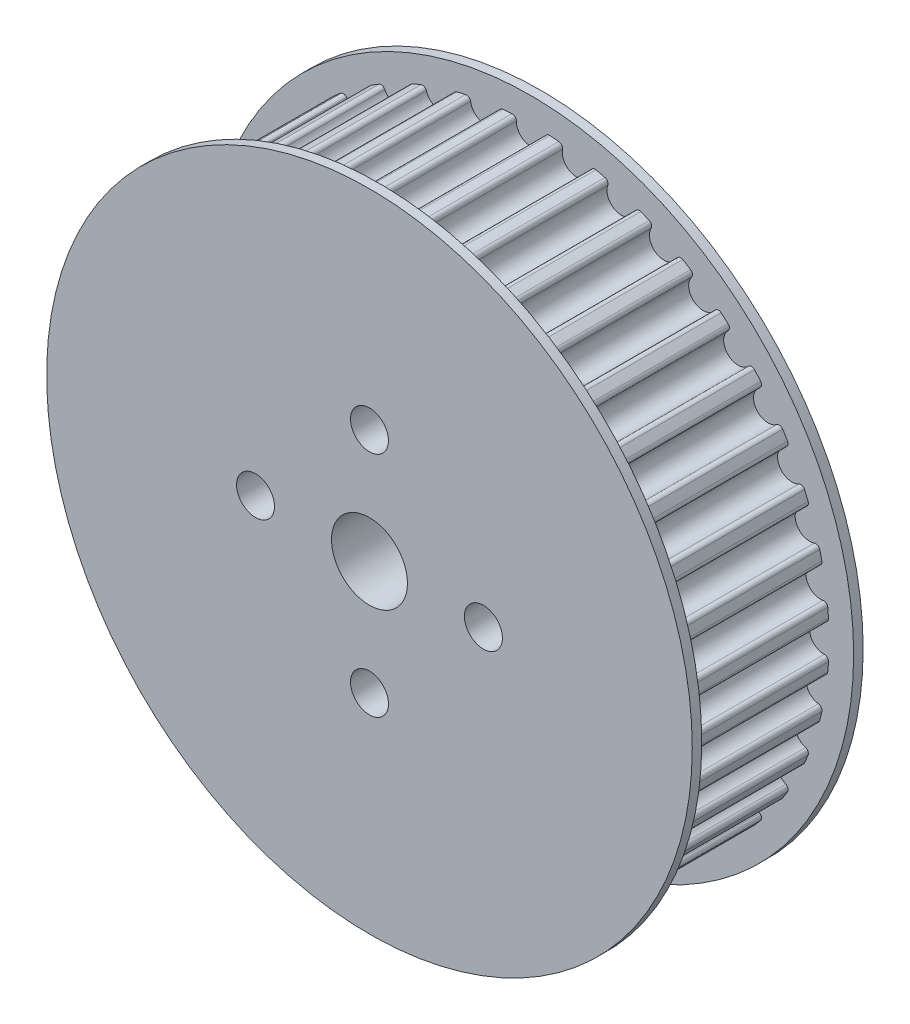
SolidWorks part; units mm, degrees
ref_plane "Front Plane" through (0, 0, 0) normal (0, 0, 1) x (1, 0, 0)
ref_plane "Top Plane" through (0, 0, 0) normal (0, 1, 0) x (1, 0, 0)
ref_plane "Right Plane" through (0, 0, 0) normal (1, 0, 0) x (0, 0, -1)
sketch "Sketch1" plane through (0, 0, 0) normal (0, 0, 1) x (1, 0, 0)
  line L0 (0, 0) -> (0, 52.0511) construction
  line L1 (0, 0) -> (78.6588, 0) construction
  line L2 (0, 0) -> (7.0914, 44.7731) construction
  arc A2 (0, 29.35) -> (1.5246, 30.9088) centre (0, 30.875) ccw
  arc A3 (1.9816, 31.3474) -> (1.5246, 30.9088) centre (1.9545, 30.9183) ccw
  arc A4 (3.3293, 30.7667) -> (4.5914, 28.9887) centre (4.8299, 30.4949) ccw
  arc A5 (3.3293, 30.7667) -> (2.9466, 31.2715) centre (2.9062, 30.8434) ccw
  arc A6 (2.9466, 31.2715) -> (1.9816, 31.3474) centre (0, 0) ccw
  arc A7 (4.5914, 28.9887) -> (6.3411, 30.2897) centre (4.8299, 30.4949) ccw
  arc A8 (6.8611, 30.6515) -> (6.3411, 30.2897) centre (6.7671, 30.2319) ccw
  arc A9 (7.8022, 30.4255) -> (6.8611, 30.6515) centre (0, 0) ccw
  arc A10 (8.1013, 29.8671) -> (7.8022, 30.4255) centre (7.6954, 30.009) ccw
  arc A11 (8.1013, 29.8671) -> (9.0696, 27.9135) centre (9.5409, 29.3639) ccw
  arc A12 (9.0696, 27.9135) -> (11.0013, 28.9248) centre (9.5409, 29.3639) ccw
  arc A13 (11.5715, 29.2008) -> (11.0013, 28.9248) centre (11.4131, 28.8011) ccw
  arc A14 (12.4658, 28.8304) -> (11.5715, 29.2008) centre (0, 0) ccw
  arc A15 (12.6738, 28.2321) -> (12.4658, 28.8304) centre (12.2951, 28.4357) ccw
  arc A16 (12.6738, 28.2321) -> (13.3246, 26.151) centre (14.017, 27.5098) ccw
  arc A17 (13.3246, 26.151) -> (15.3907, 26.8477) centre (14.017, 27.5098) ccw
  arc A18 (15.9971, 27.0311) -> (15.3907, 26.8477) centre (15.7781, 26.6611) ccw
  arc A19 (16.8224, 26.5254) -> (15.9971, 27.0311) centre (0, 0) ccw
  arc A20 (16.9343, 25.9019) -> (16.8224, 26.5254) centre (16.5921, 26.1623) ccw
  arc A21 (16.9343, 25.9019) -> (17.2515, 23.7446) centre (18.1479, 24.9784) ccw
  arc A22 (17.2515, 23.7446) -> (19.4012, 24.1096) centre (18.1479, 24.9784) ccw
  arc A23 (20.0287, 24.1958) -> (19.4012, 24.1096) centre (19.7546, 23.8646) ccw
  arc A24 (20.7647, 23.5672) -> (20.0287, 24.1958) centre (0, 0) ccw
  arc A25 (20.7777, 22.9339) -> (20.7647, 23.5672) centre (20.4805, 23.2446) ccw
  arc A26 (20.7777, 22.9339) -> (20.7536, 20.7536) centre (21.8319, 21.8319) ccw
  arc A27 (20.7536, 20.7536) -> (22.9339, 20.7777) centre (21.8319, 21.8319) ccw
  arc A28 (23.5672, 20.7647) -> (22.9339, 20.7777) centre (23.2446, 20.4805) ccw
  arc A29 (24.1958, 20.0287) -> (23.5672, 20.7647) centre (0, 0) ccw
  arc A30 (24.1096, 19.4012) -> (24.1958, 20.0287) centre (23.8646, 19.7546) ccw
  arc A31 (24.1096, 19.4012) -> (23.7446, 17.2515) centre (24.9784, 18.1479) ccw
  arc A32 (23.7446, 17.2515) -> (25.9019, 16.9343) centre (24.9784, 18.1479) ccw
  arc A33 (26.5254, 16.8224) -> (25.9019, 16.9343) centre (26.1623, 16.5921) ccw
  arc A34 (27.0311, 15.9971) -> (26.5254, 16.8224) centre (0, 0) ccw
  arc A35 (26.8477, 15.3907) -> (27.0311, 15.9971) centre (26.6611, 15.7781) ccw
  arc A36 (26.8477, 15.3907) -> (26.151, 13.3246) centre (27.5098, 14.017) ccw
  arc A37 (26.151, 13.3246) -> (28.2321, 12.6738) centre (27.5098, 14.017) ccw
  arc A38 (28.8304, 12.4658) -> (28.2321, 12.6738) centre (28.4357, 12.2951) ccw
  arc A39 (29.2008, 11.5715) -> (28.8304, 12.4658) centre (0, 0) ccw
  arc A40 (28.9248, 11.0013) -> (29.2008, 11.5715) centre (28.8011, 11.4131) ccw
  arc A41 (28.9248, 11.0013) -> (27.9135, 9.0696) centre (29.3639, 9.5409) ccw
  arc A42 (27.9135, 9.0696) -> (29.8671, 8.1013) centre (29.3639, 9.5409) ccw
  arc A43 (30.4255, 7.8022) -> (29.8671, 8.1013) centre (30.009, 7.6954) ccw
  arc A44 (30.6515, 6.8611) -> (30.4255, 7.8022) centre (0, 0) ccw
  arc A45 (30.2897, 6.3411) -> (30.6515, 6.8611) centre (30.2319, 6.7671) ccw
  arc A46 (30.2897, 6.3411) -> (28.9887, 4.5914) centre (30.4949, 4.8299) ccw
  arc A47 (28.9887, 4.5914) -> (30.7667, 3.3293) centre (30.4949, 4.8299) ccw
  arc A48 (31.2715, 2.9466) -> (30.7667, 3.3293) centre (30.8434, 2.9062) ccw
  arc A49 (31.3474, 1.9816) -> (31.2715, 2.9466) centre (0, 0) ccw
  arc A50 (30.9088, 1.5246) -> (31.3474, 1.9816) centre (30.9183, 1.9545) ccw
  arc A51 (30.9088, 1.5246) -> (29.35, 0) centre (30.875, 0) ccw
  arc A52 (29.35, 0) -> (30.9088, -1.5246) centre (30.875, 0) ccw
  arc A53 (31.3474, -1.9816) -> (30.9088, -1.5246) centre (30.9183, -1.9545) ccw
  arc A54 (31.2715, -2.9466) -> (31.3474, -1.9816) centre (0, 0) ccw
  arc A55 (30.7667, -3.3293) -> (31.2715, -2.9466) centre (30.8434, -2.9062) ccw
  arc A56 (30.7667, -3.3293) -> (28.9887, -4.5914) centre (30.4949, -4.8299) ccw
  arc A57 (28.9887, -4.5914) -> (30.2897, -6.3411) centre (30.4949, -4.8299) ccw
  arc A58 (30.6515, -6.8611) -> (30.2897, -6.3411) centre (30.2319, -6.7671) ccw
  arc A59 (30.4255, -7.8022) -> (30.6515, -6.8611) centre (0, 0) ccw
  arc A60 (29.8671, -8.1013) -> (30.4255, -7.8022) centre (30.009, -7.6954) ccw
  arc A61 (29.8671, -8.1013) -> (27.9135, -9.0696) centre (29.3639, -9.5409) ccw
  arc A62 (27.9135, -9.0696) -> (28.9248, -11.0013) centre (29.3639, -9.5409) ccw
  arc A63 (29.2008, -11.5715) -> (28.9248, -11.0013) centre (28.8011, -11.4131) ccw
  arc A64 (28.8304, -12.4658) -> (29.2008, -11.5715) centre (0, 0) ccw
  arc A65 (28.2321, -12.6738) -> (28.8304, -12.4658) centre (28.4357, -12.2951) ccw
  arc A66 (28.2321, -12.6738) -> (26.151, -13.3246) centre (27.5098, -14.017) ccw
  arc A67 (26.151, -13.3246) -> (26.8477, -15.3907) centre (27.5098, -14.017) ccw
  arc A68 (27.0311, -15.9971) -> (26.8477, -15.3907) centre (26.6611, -15.7781) ccw
  arc A69 (26.5254, -16.8224) -> (27.0311, -15.9971) centre (0, 0) ccw
  arc A70 (25.9019, -16.9343) -> (26.5254, -16.8224) centre (26.1623, -16.5921) ccw
  arc A71 (25.9019, -16.9343) -> (23.7446, -17.2515) centre (24.9784, -18.1479) ccw
  arc A72 (23.7446, -17.2515) -> (24.1096, -19.4012) centre (24.9784, -18.1479) ccw
  arc A73 (24.1958, -20.0287) -> (24.1096, -19.4012) centre (23.8646, -19.7546) ccw
  arc A74 (23.5672, -20.7647) -> (24.1958, -20.0287) centre (0, 0) ccw
  arc A75 (22.9339, -20.7777) -> (23.5672, -20.7647) centre (23.2446, -20.4805) ccw
  arc A76 (22.9339, -20.7777) -> (20.7536, -20.7536) centre (21.8319, -21.8319) ccw
  arc A77 (20.7536, -20.7536) -> (20.7777, -22.9339) centre (21.8319, -21.8319) ccw
  arc A78 (20.7647, -23.5672) -> (20.7777, -22.9339) centre (20.4805, -23.2446) ccw
  arc A79 (20.0287, -24.1958) -> (20.7647, -23.5672) centre (0, 0) ccw
  arc A80 (19.4012, -24.1096) -> (20.0287, -24.1958) centre (19.7546, -23.8646) ccw
  arc A81 (19.4012, -24.1096) -> (17.2515, -23.7446) centre (18.1479, -24.9784) ccw
  arc A82 (17.2515, -23.7446) -> (16.9343, -25.9019) centre (18.1479, -24.9784) ccw
  arc A83 (16.8224, -26.5254) -> (16.9343, -25.9019) centre (16.5921, -26.1623) ccw
  arc A84 (15.9971, -27.0311) -> (16.8224, -26.5254) centre (0, 0) ccw
  arc A85 (15.3907, -26.8477) -> (15.9971, -27.0311) centre (15.7781, -26.6611) ccw
  arc A86 (15.3907, -26.8477) -> (13.3246, -26.151) centre (14.017, -27.5098) ccw
  arc A87 (13.3246, -26.151) -> (12.6738, -28.2321) centre (14.017, -27.5098) ccw
  arc A88 (12.4658, -28.8304) -> (12.6738, -28.2321) centre (12.2951, -28.4357) ccw
  arc A89 (11.5715, -29.2008) -> (12.4658, -28.8304) centre (0, 0) ccw
  arc A90 (11.0013, -28.9248) -> (11.5715, -29.2008) centre (11.4131, -28.8011) ccw
  arc A91 (11.0013, -28.9248) -> (9.0696, -27.9135) centre (9.5409, -29.3639) ccw
  arc A92 (9.0696, -27.9135) -> (8.1013, -29.8671) centre (9.5409, -29.3639) ccw
  arc A93 (7.8022, -30.4255) -> (8.1013, -29.8671) centre (7.6954, -30.009) ccw
  arc A94 (6.8611, -30.6515) -> (7.8022, -30.4255) centre (0, 0) ccw
  arc A95 (6.3411, -30.2897) -> (6.8611, -30.6515) centre (6.7671, -30.2319) ccw
  arc A96 (6.3411, -30.2897) -> (4.5914, -28.9887) centre (4.8299, -30.4949) ccw
  arc A97 (4.5914, -28.9887) -> (3.3293, -30.7667) centre (4.8299, -30.4949) ccw
  arc A98 (2.9466, -31.2715) -> (3.3293, -30.7667) centre (2.9062, -30.8434) ccw
  arc A99 (1.9816, -31.3474) -> (2.9466, -31.2715) centre (0, 0) ccw
  arc A100 (1.5246, -30.9088) -> (1.9816, -31.3474) centre (1.9545, -30.9183) ccw
  arc A101 (1.5246, -30.9088) -> (0, -29.35) centre (0, -30.875) ccw
  arc A102 (0, -29.35) -> (-1.5246, -30.9088) centre (0, -30.875) ccw
  arc A103 (-1.9816, -31.3474) -> (-1.5246, -30.9088) centre (-1.9545, -30.9183) ccw
  arc A104 (-2.9466, -31.2715) -> (-1.9816, -31.3474) centre (0, 0) ccw
  arc A105 (-3.3293, -30.7667) -> (-2.9466, -31.2715) centre (-2.9062, -30.8434) ccw
  arc A106 (-3.3293, -30.7667) -> (-4.5914, -28.9887) centre (-4.8299, -30.4949) ccw
  arc A107 (-4.5914, -28.9887) -> (-6.3411, -30.2897) centre (-4.8299, -30.4949) ccw
  arc A108 (-6.8611, -30.6515) -> (-6.3411, -30.2897) centre (-6.7671, -30.2319) ccw
  arc A109 (-7.8022, -30.4255) -> (-6.8611, -30.6515) centre (0, 0) ccw
  arc A110 (-8.1013, -29.8671) -> (-7.8022, -30.4255) centre (-7.6954, -30.009) ccw
  arc A111 (-8.1013, -29.8671) -> (-9.0696, -27.9135) centre (-9.5409, -29.3639) ccw
  arc A112 (-9.0696, -27.9135) -> (-11.0013, -28.9248) centre (-9.5409, -29.3639) ccw
  arc A113 (-11.5715, -29.2008) -> (-11.0013, -28.9248) centre (-11.4131, -28.8011) ccw
  arc A114 (-12.4658, -28.8304) -> (-11.5715, -29.2008) centre (0, 0) ccw
  arc A115 (-12.6738, -28.2321) -> (-12.4658, -28.8304) centre (-12.2951, -28.4357) ccw
  arc A116 (-12.6738, -28.2321) -> (-13.3246, -26.151) centre (-14.017, -27.5098) ccw
  arc A117 (-13.3246, -26.151) -> (-15.3907, -26.8477) centre (-14.017, -27.5098) ccw
  arc A118 (-15.9971, -27.0311) -> (-15.3907, -26.8477) centre (-15.7781, -26.6611) ccw
  arc A119 (-16.8224, -26.5254) -> (-15.9971, -27.0311) centre (0, 0) ccw
  arc A120 (-16.9343, -25.9019) -> (-16.8224, -26.5254) centre (-16.5921, -26.1623) ccw
  arc A121 (-16.9343, -25.9019) -> (-17.2515, -23.7446) centre (-18.1479, -24.9784) ccw
  arc A122 (-17.2515, -23.7446) -> (-19.4012, -24.1096) centre (-18.1479, -24.9784) ccw
  arc A123 (-20.0287, -24.1958) -> (-19.4012, -24.1096) centre (-19.7546, -23.8646) ccw
  arc A124 (-20.7647, -23.5672) -> (-20.0287, -24.1958) centre (0, 0) ccw
  arc A125 (-20.7777, -22.9339) -> (-20.7647, -23.5672) centre (-20.4805, -23.2446) ccw
  arc A126 (-20.7777, -22.9339) -> (-20.7536, -20.7536) centre (-21.8319, -21.8319) ccw
  arc A127 (-20.7536, -20.7536) -> (-22.9339, -20.7777) centre (-21.8319, -21.8319) ccw
  arc A128 (-23.5672, -20.7647) -> (-22.9339, -20.7777) centre (-23.2446, -20.4805) ccw
  arc A129 (-24.1958, -20.0287) -> (-23.5672, -20.7647) centre (0, 0) ccw
  arc A130 (-24.1096, -19.4012) -> (-24.1958, -20.0287) centre (-23.8646, -19.7546) ccw
  arc A131 (-24.1096, -19.4012) -> (-23.7446, -17.2515) centre (-24.9784, -18.1479) ccw
  arc A132 (-23.7446, -17.2515) -> (-25.9019, -16.9343) centre (-24.9784, -18.1479) ccw
  arc A133 (-26.5254, -16.8224) -> (-25.9019, -16.9343) centre (-26.1623, -16.5921) ccw
  arc A134 (-27.0311, -15.9971) -> (-26.5254, -16.8224) centre (0, 0) ccw
  arc A135 (-26.8477, -15.3907) -> (-27.0311, -15.9971) centre (-26.6611, -15.7781) ccw
  arc A136 (-26.8477, -15.3907) -> (-26.151, -13.3246) centre (-27.5098, -14.017) ccw
  arc A137 (-26.151, -13.3246) -> (-28.2321, -12.6738) centre (-27.5098, -14.017) ccw
  arc A138 (-28.8304, -12.4658) -> (-28.2321, -12.6738) centre (-28.4357, -12.2951) ccw
  arc A139 (-29.2008, -11.5715) -> (-28.8304, -12.4658) centre (0, 0) ccw
  arc A140 (-28.9248, -11.0013) -> (-29.2008, -11.5715) centre (-28.8011, -11.4131) ccw
  arc A141 (-28.9248, -11.0013) -> (-27.9135, -9.0696) centre (-29.3639, -9.5409) ccw
  arc A142 (-27.9135, -9.0696) -> (-29.8671, -8.1013) centre (-29.3639, -9.5409) ccw
  arc A143 (-30.4255, -7.8022) -> (-29.8671, -8.1013) centre (-30.009, -7.6954) ccw
  arc A144 (-30.6515, -6.8611) -> (-30.4255, -7.8022) centre (0, 0) ccw
  arc A145 (-30.2897, -6.3411) -> (-30.6515, -6.8611) centre (-30.2319, -6.7671) ccw
  arc A146 (-30.2897, -6.3411) -> (-28.9887, -4.5914) centre (-30.4949, -4.8299) ccw
  arc A147 (-28.9887, -4.5914) -> (-30.7667, -3.3293) centre (-30.4949, -4.8299) ccw
  arc A148 (-31.2715, -2.9466) -> (-30.7667, -3.3293) centre (-30.8434, -2.9062) ccw
  arc A149 (-31.3474, -1.9816) -> (-31.2715, -2.9466) centre (0, 0) ccw
  arc A150 (-30.9088, -1.5246) -> (-31.3474, -1.9816) centre (-30.9183, -1.9545) ccw
  arc A151 (-30.9088, -1.5246) -> (-29.35, 0) centre (-30.875, 0) ccw
  arc A152 (-29.35, 0) -> (-30.9088, 1.5246) centre (-30.875, 0) ccw
  arc A153 (-31.3474, 1.9816) -> (-30.9088, 1.5246) centre (-30.9183, 1.9545) ccw
  arc A154 (-31.2715, 2.9466) -> (-31.3474, 1.9816) centre (0, 0) ccw
  arc A155 (-30.7667, 3.3293) -> (-31.2715, 2.9466) centre (-30.8434, 2.9062) ccw
  arc A156 (-30.7667, 3.3293) -> (-28.9887, 4.5914) centre (-30.4949, 4.8299) ccw
  arc A157 (-28.9887, 4.5914) -> (-30.2897, 6.3411) centre (-30.4949, 4.8299) ccw
  arc A158 (-30.6515, 6.8611) -> (-30.2897, 6.3411) centre (-30.2319, 6.7671) ccw
  arc A159 (-30.4255, 7.8022) -> (-30.6515, 6.8611) centre (0, 0) ccw
  arc A160 (-29.8671, 8.1013) -> (-30.4255, 7.8022) centre (-30.009, 7.6954) ccw
  arc A161 (-29.8671, 8.1013) -> (-27.9135, 9.0696) centre (-29.3639, 9.5409) ccw
  arc A162 (-27.9135, 9.0696) -> (-28.9248, 11.0013) centre (-29.3639, 9.5409) ccw
  arc A163 (-29.2008, 11.5715) -> (-28.9248, 11.0013) centre (-28.8011, 11.4131) ccw
  arc A164 (-28.8304, 12.4658) -> (-29.2008, 11.5715) centre (0, 0) ccw
  arc A165 (-28.2321, 12.6738) -> (-28.8304, 12.4658) centre (-28.4357, 12.2951) ccw
  arc A166 (-28.2321, 12.6738) -> (-26.151, 13.3246) centre (-27.5098, 14.017) ccw
  arc A167 (-26.151, 13.3246) -> (-26.8477, 15.3907) centre (-27.5098, 14.017) ccw
  arc A168 (-27.0311, 15.9971) -> (-26.8477, 15.3907) centre (-26.6611, 15.7781) ccw
  arc A169 (-26.5254, 16.8224) -> (-27.0311, 15.9971) centre (0, 0) ccw
  arc A170 (-25.9019, 16.9343) -> (-26.5254, 16.8224) centre (-26.1623, 16.5921) ccw
  arc A171 (-25.9019, 16.9343) -> (-23.7446, 17.2515) centre (-24.9784, 18.1479) ccw
  arc A172 (-23.7446, 17.2515) -> (-24.1096, 19.4012) centre (-24.9784, 18.1479) ccw
  arc A173 (-24.1958, 20.0287) -> (-24.1096, 19.4012) centre (-23.8646, 19.7546) ccw
  arc A174 (-23.5672, 20.7647) -> (-24.1958, 20.0287) centre (0, 0) ccw
  arc A175 (-22.9339, 20.7777) -> (-23.5672, 20.7647) centre (-23.2446, 20.4805) ccw
  arc A176 (-22.9339, 20.7777) -> (-20.7536, 20.7536) centre (-21.8319, 21.8319) ccw
  arc A177 (-20.7536, 20.7536) -> (-20.7777, 22.9339) centre (-21.8319, 21.8319) ccw
  arc A178 (-20.7647, 23.5672) -> (-20.7777, 22.9339) centre (-20.4805, 23.2446) ccw
  arc A179 (-20.0287, 24.1958) -> (-20.7647, 23.5672) centre (0, 0) ccw
  arc A180 (-19.4012, 24.1096) -> (-20.0287, 24.1958) centre (-19.7546, 23.8646) ccw
  arc A181 (-19.4012, 24.1096) -> (-17.2515, 23.7446) centre (-18.1479, 24.9784) ccw
  arc A182 (-17.2515, 23.7446) -> (-16.9343, 25.9019) centre (-18.1479, 24.9784) ccw
  arc A183 (-16.8224, 26.5254) -> (-16.9343, 25.9019) centre (-16.5921, 26.1623) ccw
  arc A184 (-15.9971, 27.0311) -> (-16.8224, 26.5254) centre (0, 0) ccw
  arc A185 (-15.3907, 26.8477) -> (-15.9971, 27.0311) centre (-15.7781, 26.6611) ccw
  arc A186 (-15.3907, 26.8477) -> (-13.3246, 26.151) centre (-14.017, 27.5098) ccw
  arc A187 (-13.3246, 26.151) -> (-12.6738, 28.2321) centre (-14.017, 27.5098) ccw
  arc A188 (-12.4658, 28.8304) -> (-12.6738, 28.2321) centre (-12.2951, 28.4357) ccw
  arc A189 (-11.5715, 29.2008) -> (-12.4658, 28.8304) centre (0, 0) ccw
  arc A190 (-11.0013, 28.9248) -> (-11.5715, 29.2008) centre (-11.4131, 28.8011) ccw
  arc A191 (-11.0013, 28.9248) -> (-9.0696, 27.9135) centre (-9.5409, 29.3639) ccw
  arc A192 (-9.0696, 27.9135) -> (-8.1013, 29.8671) centre (-9.5409, 29.3639) ccw
  arc A193 (-7.8022, 30.4255) -> (-8.1013, 29.8671) centre (-7.6954, 30.009) ccw
  arc A194 (-6.8611, 30.6515) -> (-7.8022, 30.4255) centre (0, 0) ccw
  arc A195 (-6.3411, 30.2897) -> (-6.8611, 30.6515) centre (-6.7671, 30.2319) ccw
  arc A196 (-6.3411, 30.2897) -> (-4.5914, 28.9887) centre (-4.8299, 30.4949) ccw
  arc A197 (-4.5914, 28.9887) -> (-3.3293, 30.7667) centre (-4.8299, 30.4949) ccw
  arc A198 (-2.9466, 31.2715) -> (-3.3293, 30.7667) centre (-2.9062, 30.8434) ccw
  arc A199 (-1.9816, 31.3474) -> (-2.9466, 31.2715) centre (0, 0) ccw
  arc A200 (-1.5246, 30.9088) -> (-1.9816, 31.3474) centre (-1.9545, 30.9183) ccw
  arc A201 (-1.5246, 30.9088) -> (0, 29.35) centre (0, 30.875) ccw
  point P409 (0, 0)
  dimension "D1" = 40
  dimension "D3" = 3.05
  dimension "D4" = 0.86
  dimension "D6" = 3.05
  dimension "D7" = 0.86
extrude "Boss-Extrude1" add sketch "Sketch1" along normal blind 16
sketch "Sketch2" plane through (0, 0, 16) normal (0, 0, 1) x (1, 0, 0)
  circle A0 centre (0, 0) radius 34
  dimension "D1" = 68
extrude "Boss-Extrude2" add sketch "Sketch2" along normal blind 1
ref_plane "Plane1" through (0, 0, 8) normal (0, 0, -1) x (-1, 0, 0)
mirror "Mirror1" about plane through (0, 0, 8) normal (0, 0, -1) of "Boss-Extrude2"
sketch "Sketch3" plane through (0, 0, 17) normal (0, 0, 1) x (1, 0, 0)
  circle A0 centre (0, 0) radius 4
  circle A1 centre (12, 0) radius 2
  circle A2 centre (0, -12) radius 2
  circle A3 centre (-12, 0) radius 2
  circle A4 centre (0, 12) radius 2
  point P14 (0, 0)
  dimension "D1" = 8
  dimension "D3" = 4
  dimension "D2" = 12
  dimension "D4" = 4
extrude "Cut-Extrude1" cut sketch "Sketch3" against normal through all
sketch "Sketch4" plane through (0, 0, 17) normal (0, 0, 1) x (1, 0, 0)
  line L0 (0, 12) -> (0, -12) construction
